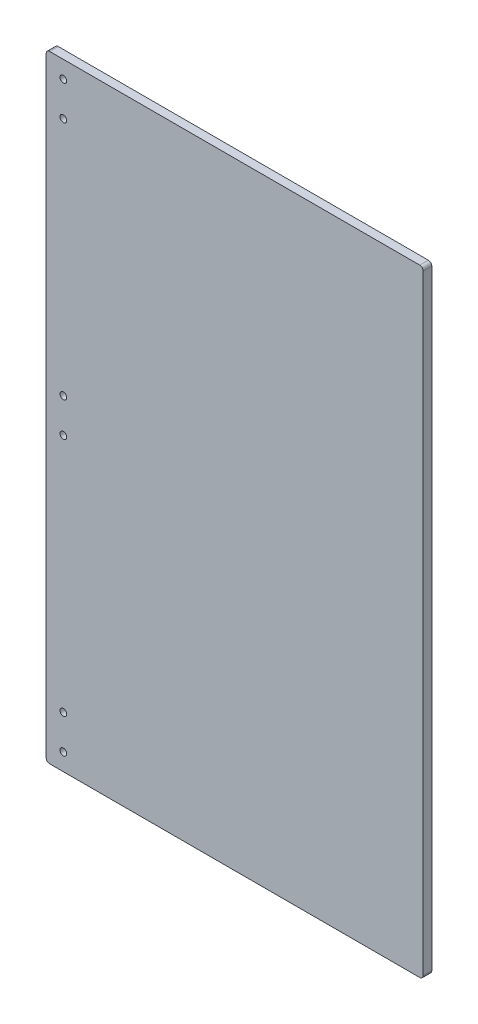
SolidWorks part; units mm, degrees
ref_plane "Front Plane" through (0, 0, 0) normal (0, 0, 1) x (1, 0, 0)
ref_plane "Top Plane" through (0, 0, 0) normal (0, 1, 0) x (1, 0, 0)
ref_plane "Right Plane" through (0, 0, 0) normal (1, 0, 0) x (0, 0, -1)
sketch "Sketch1" plane through (0, 0, 0) normal (0, 0, 1) x (1, 0, 0)
  line L0 (0, 0) -> (279.4, 0)
  line L1 (0, 0) -> (0, 457.2)
  line L2 (279.4, 0) -> (279.4, 457.2)
  line L3 (0, 457.2) -> (279.4, 457.2)
  line L4 (12.7, 444.5) -> (12.7, 419.1) construction
  line L5 (12.7, 241.3) -> (12.7, 215.9) construction
  line L6 (12.7, 12.7) -> (12.7, 38.1) construction
  line L7 (0, 228.6) -> (12.7, 228.6) construction
  circle A0 centre (12.7, 444.5) radius 2.5
  circle A1 centre (12.7, 419.1) radius 2.5
  circle A2 centre (12.7, 241.3) radius 2.5
  circle A3 centre (12.7, 215.9) radius 2.5
  circle A4 centre (12.7, 38.1) radius 2.5
  circle A5 centre (12.7, 12.7) radius 2.5
  dimension "D3" = 5
  dimension "D1" = 457.2
  dimension "D2" = 279.4
  dimension "D4" = 12.7
  dimension "D5" = 25.4
  dimension "D6" = 12.7
  dimension "D7" = 12.7
extrude "Boss-Extrude1" add sketch "Sketch1" along normal blind 6.35
fillet "Fillet1" radius 2.54 4 edges at (0, 457.2, 3.175) (0, 0, 3.175) (279.4, 0, 3.175) (279.4, 457.2, 3.175)
